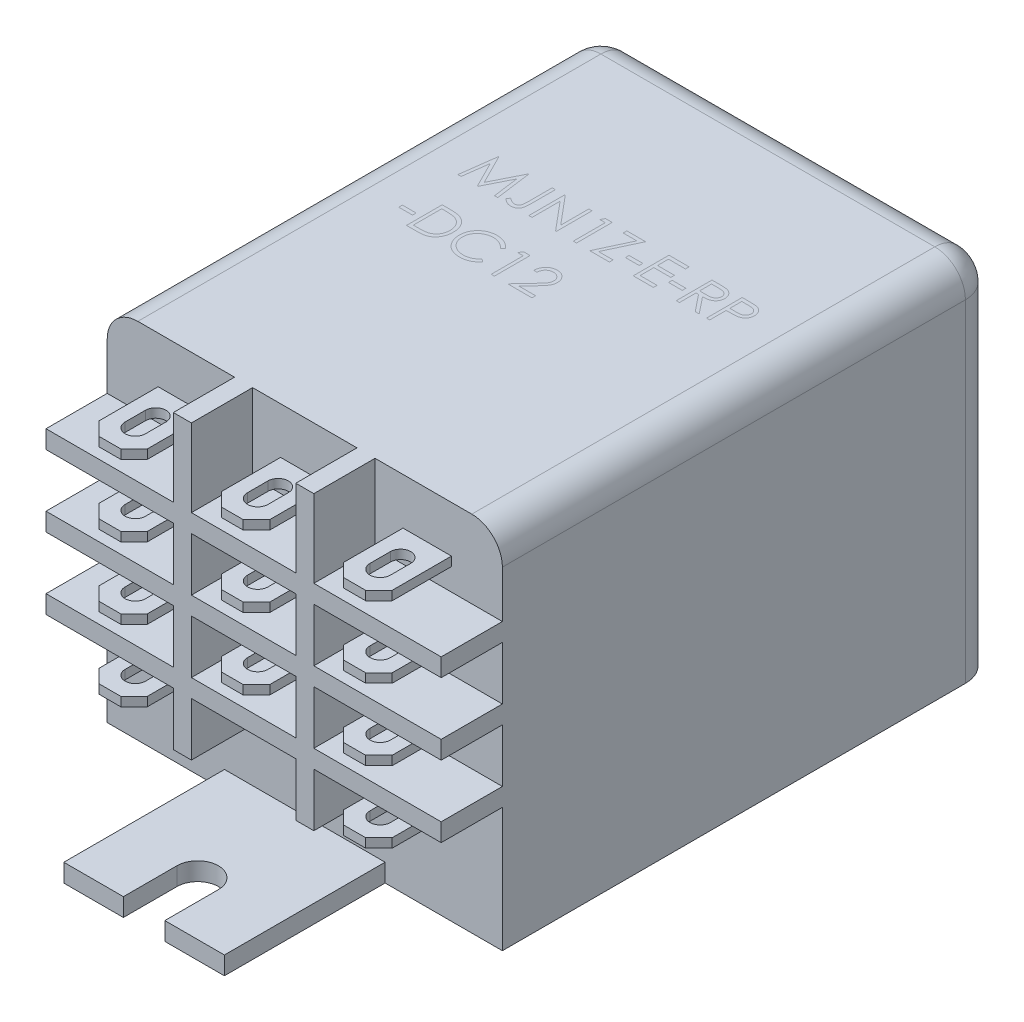
SolidWorks part; units mm, degrees
material "ABS"
ref_plane "Ground_Plane" through (0, 0, 0) normal (0, 0, 1) x (1, 0, 0)
ref_plane "VehicleCentre_Plane" through (0, 0, 0) normal (0, 1, 0) x (1, 0, 0)
ref_plane "FrontAxle_Plane" through (0, 0, 0) normal (1, 0, 0) x (0, 0, -1)
sketch "Sketch1" plane through (0, 0, 0) normal (0, 1, 0) x (1, 0, 0)
  line L1 (19.365, 24.19) -> (-19.365, 24.19)
  line L2 (19.365, 24.19) -> (19.365, -24.19)
  line L3 (19.365, -24.19) -> (-19.365, -24.19)
  line L4 (-19.365, 24.19) -> (-19.365, -24.19)
  line L5 (19.365, 24.19) -> (-19.365, -24.19) construction
  line L6 (19.365, -24.19) -> (-19.365, 24.19) construction
  point P0 (0, 0)
  dimension "D1" = 38.73
  dimension "D2" = 48.38
extrude "Boss-Extrude1" add sketch "Sketch1" along normal blind 35.56
sketch "Sketch2" plane through (0, 0, 0) normal (0, 1, 0) x (1, 0, 0)
  line L0 (-7.87, 24.19) -> (7.87, 24.19)
  line L1 (19.365, 24.19) -> (-19.365, 24.19) construction
  line L2 (7.87, 24.19) -> (7.87, 33.72)
  line L3 (7.87, 33.72) -> (2.03, 33.72)
  line L4 (2.03, 33.72) -> (2.03, 28.81)
  line L5 (-7.87, 24.19) -> (-7.87, 33.72)
  line L6 (-7.87, 33.72) -> (-2.03, 33.72)
  line L7 (-2.03, 33.72) -> (-2.03, 28.81)
  line L8 (7.87, -24.19) -> (-7.87, -24.19)
  line L9 (-7.87, -24.19) -> (-7.87, -39.94)
  line L10 (-7.87, -39.94) -> (-2.03, -39.94)
  line L11 (-2.03, -39.94) -> (-2.03, -34.69)
  line L12 (7.87, -24.19) -> (7.87, -39.94)
  line L13 (7.87, -39.94) -> (2.03, -39.94)
  line L14 (2.03, -39.94) -> (2.03, -34.69)
  line L15 (-19.365, -24.19) -> (19.365, -24.19) construction
  arc A0 (-2.03, 28.81) -> (2.03, 28.81) centre (0, 28.81) ccw
  arc A1 (2.03, -34.69) -> (-2.03, -34.69) centre (0, -34.69) ccw
  point P23 (0, 0)
  dimension "D2" = 2.03
  dimension "D1" = 15.74
  dimension "D3" = 9.53
  dimension "D4" = 10.5
  dimension "D5" = 73.66
  dimension "D6" = 63.5
extrude "Boss-Extrude2" add sketch "Sketch2" along normal blind 1.77
sketch "Sketch3" plane through (0, 0, 24.19) normal (0, 0, 1) x (1, 0, 0)
  line L0 (-19.365, 35.56) -> (19.365, 35.56) construction
  line L1 (-2.3749, 31.0045) -> (2.3749, 31.0045)
  line L2 (-2.3749, 31.0045) -> (-2.3749, 30.1155)
  line L3 (-2.3749, 30.1155) -> (2.3749, 30.1155)
  line L4 (2.3749, 31.0045) -> (2.3749, 30.1155)
  line L5 (-2.3749, 31.0045) -> (2.3749, 30.1155) construction
  line L6 (-2.3749, 30.1155) -> (2.3749, 31.0045) construction
  line L7 (9.6251, 31.0045) -> (9.6251, 30.1155)
  line L8 (9.6251, 31.0045) -> (14.3749, 31.0045)
  line L9 (14.3749, 31.0045) -> (14.3749, 30.1155)
  line L10 (9.6251, 30.1155) -> (14.3749, 30.1155)
  line L11 (9.6251, 24.0045) -> (9.6251, 23.1155)
  line L12 (9.6251, 24.0045) -> (14.3749, 24.0045)
  line L13 (14.3749, 24.0045) -> (14.3749, 23.1155)
  line L14 (9.6251, 23.1155) -> (14.3749, 23.1155)
  line L15 (9.6251, 17.0045) -> (9.6251, 16.1155)
  line L16 (9.6251, 17.0045) -> (14.3749, 17.0045)
  line L17 (14.3749, 17.0045) -> (14.3749, 16.1155)
  line L18 (9.6251, 16.1155) -> (14.3749, 16.1155)
  line L19 (9.6251, 10.0045) -> (9.6251, 9.1155)
  line L20 (9.6251, 10.0045) -> (14.3749, 10.0045)
  line L21 (14.3749, 10.0045) -> (14.3749, 9.1155)
  line L22 (9.6251, 9.1155) -> (14.3749, 9.1155)
  line L23 (-2.3749, 24.0045) -> (-2.3749, 23.1155)
  line L24 (-2.3749, 24.0045) -> (2.3749, 24.0045)
  line L25 (2.3749, 24.0045) -> (2.3749, 23.1155)
  line L26 (-2.3749, 23.1155) -> (2.3749, 23.1155)
  line L27 (-2.3749, 17.0045) -> (-2.3749, 16.1155)
  line L28 (-2.3749, 17.0045) -> (2.3749, 17.0045)
  line L29 (2.3749, 17.0045) -> (2.3749, 16.1155)
  line L30 (-2.3749, 16.1155) -> (2.3749, 16.1155)
  line L35 (-2.3749, 31.0045) -> (9.6251, 31.0045) construction
  line L36 (-2.3749, 31.0045) -> (-2.3749, 24.0045) construction
  line L37 (-14.3749, 31.0045) -> (-14.3749, 30.1155)
  line L38 (-14.3749, 31.0045) -> (-9.6251, 31.0045)
  line L39 (-9.6251, 31.0045) -> (-9.6251, 30.1155)
  line L40 (-14.3749, 30.1155) -> (-9.6251, 30.1155)
  line L41 (-14.3749, 24.0045) -> (-14.3749, 23.1155)
  line L42 (-14.3749, 24.0045) -> (-9.6251, 24.0045)
  line L43 (-9.6251, 24.0045) -> (-9.6251, 23.1155)
  line L44 (-14.3749, 23.1155) -> (-9.6251, 23.1155)
  line L45 (-14.3749, 17.0045) -> (-14.3749, 16.1155)
  line L46 (-14.3749, 17.0045) -> (-9.6251, 17.0045)
  line L47 (-9.6251, 17.0045) -> (-9.6251, 16.1155)
  line L48 (-14.3749, 16.1155) -> (-9.6251, 16.1155)
  line L49 (-14.3749, 10.0045) -> (-14.3749, 9.1155)
  line L50 (-14.3749, 10.0045) -> (-9.6251, 10.0045)
  line L51 (-9.6251, 10.0045) -> (-9.6251, 9.1155)
  line L52 (-14.3749, 9.1155) -> (-9.6251, 9.1155)
  line L53 (-2.3749, 24.0045) -> (-2.3749, 23.1155) [skipped]
  line L54 (-2.3749, 24.0045) -> (2.3749, 24.0045) [skipped]
  line L55 (2.3749, 24.0045) -> (2.3749, 23.1155) [skipped]
  line L56 (-2.3749, 23.1155) -> (2.3749, 23.1155) [skipped]
  line L57 (-2.3749, 17.0045) -> (-2.3749, 16.1155) [skipped]
  line L58 (-2.3749, 17.0045) -> (2.3749, 17.0045) [skipped]
  line L59 (2.3749, 17.0045) -> (2.3749, 16.1155) [skipped]
  line L60 (-2.3749, 16.1155) -> (2.3749, 16.1155) [skipped]
  line L61 (-2.3749, 10.0045) -> (-2.3749, 9.1155) [skipped]
  line L62 (-2.3749, 10.0045) -> (2.3749, 10.0045) [skipped]
  line L63 (2.3749, 10.0045) -> (2.3749, 9.1155) [skipped]
  line L64 (-2.3749, 9.1155) -> (2.3749, 9.1155) [skipped]
  line L65 (-2.3749, 31.0045) -> (-14.3749, 31.0045) construction
  line L66 (-2.3749, 31.0045) -> (-2.3749, 24.0045) construction
  line L67 (-2.3749, 9.1155) -> (2.3749, 9.1155) [skipped]
  line L68 (-2.3749, 10.0045) -> (-2.3749, 9.1155) [skipped]
  line L69 (-2.3749, 10.0045) -> (2.3749, 10.0045) [skipped]
  line L70 (2.3749, 10.0045) -> (2.3749, 9.1155) [skipped]
  point P0 (0, 30.56)
  point P6 (0, 0)
  point P11 (0, 0)
  point P34 (0, 0)
  dimension "D1" = 0.889
  dimension "D2" = 4.7498
  dimension "D3" = 5
  dimension "D6" = 12
  dimension "D7" = 7
  dimension "D10" = 12
  dimension "D11" = 7
  dimension "D4" = 2
  dimension "D5" = 4
  dimension "D8" = 2
  dimension "D9" = 4
extrude "Boss-Extrude3" add sketch "Sketch3" along normal blind 7.11 separate body
sketch "Sketch4" plane through (0, 31.0045, 0) normal (0, 1, 0) x (1, 0, 0)
  line L0 (-14.8749, -29.5) -> (-12.5749, -31.8)
  line L1 (-12.5749, -31.8) -> (-11.4251, -31.8)
  line L2 (-11.4251, -31.8) -> (-9.1251, -29.5)
  line L3 (-9.1251, -29.5) -> (-9.1251, -32.8)
  line L4 (-9.1251, -32.8) -> (-14.8749, -32.8)
  line L5 (-14.8749, -32.8) -> (-14.8749, -29.5)
  line L6 (-9.6251, -31.3) -> (-14.3749, -31.3) construction
  line L7 (-14.3749, -31.3) -> (-14.3749, -24.19) construction
  line L8 (-9.6251, -31.3) -> (-9.6251, -24.19) construction
  line L9 (-12, -26.8) -> (-12, -28.8) construction
  line L10 (-11, -26.8) -> (-11, -28.8)
  line L11 (-13, -26.8) -> (-13, -28.8)
  line L12 (-2.8749, -32.8) -> (-2.8749, -29.5)
  line L13 (-2.8749, -29.5) -> (-0.5749, -31.8)
  line L14 (-0.5749, -31.8) -> (0.5749, -31.8)
  line L15 (0.5749, -31.8) -> (2.8749, -29.5)
  line L16 (2.8749, -29.5) -> (2.8749, -32.8)
  line L17 (2.8749, -32.8) -> (-2.8749, -32.8)
  line L18 (0, -26.8) -> (0, -28.8) construction
  line L19 (1, -26.8) -> (1, -28.8)
  line L20 (-1, -26.8) -> (-1, -28.8)
  line L21 (9.1251, -32.8) -> (9.1251, -29.5)
  line L22 (9.1251, -29.5) -> (11.4251, -31.8)
  line L23 (11.4251, -31.8) -> (12.5749, -31.8)
  line L24 (12.5749, -31.8) -> (14.8749, -29.5)
  line L25 (14.8749, -29.5) -> (14.8749, -32.8)
  line L26 (14.8749, -32.8) -> (9.1251, -32.8)
  line L27 (12, -26.8) -> (12, -28.8) construction
  line L28 (13, -26.8) -> (13, -28.8)
  line L29 (11, -26.8) -> (11, -28.8)
  line L30 (-14.8749, -32.8) -> (-2.8749, -32.8) construction
  arc A0 (-11, -26.8) -> (-13, -26.8) centre (-12, -26.8) ccw
  arc A1 (-13, -28.8) -> (-11, -28.8) centre (-12, -28.8) ccw
  arc A2 (1, -26.8) -> (-1, -26.8) centre (0, -26.8) ccw
  arc A3 (-1, -28.8) -> (1, -28.8) centre (0, -28.8) ccw
  arc A4 (13, -26.8) -> (11, -26.8) centre (12, -26.8) ccw
  arc A5 (11, -28.8) -> (13, -28.8) centre (12, -28.8) ccw
  point P10 (-12, -27.8)
  point P19 (-12, -31.3)
  point P28 (0, -27.8)
  point P41 (12, -27.8)
  dimension "D7" = 1
  dimension "D1" = 0.5
  dimension "D2" = 0.5
  dimension "D3" = 135
  dimension "D4" = 0.5
  dimension "D5" = 1.8
  dimension "D6" = 1
  dimension "D8" = 2
  dimension "D9" = 3.5
  dimension "D11" = 12
  dimension "D10" = 3
extrude "Cut-Extrude1" cut sketch "Sketch4" against normal blind 26
sketch "Sketch5" plane through (0, 0, 24.19) normal (0, 0, 1) x (1, 0, 0)
  line L0 (-19.365, 27.945) -> (-6.885, 27.945)
  line L1 (-19.365, 35.56) -> (-19.365, 0) construction
  line L2 (-6.885, 27.945) -> (-6.885, 35.56)
  line L3 (-19.365, 35.56) -> (19.365, 35.56) construction
  line L4 (-6.885, 35.56) -> (-5.115, 35.56)
  line L5 (-5.115, 35.56) -> (-5.115, 27.945)
  line L6 (-5.115, 27.945) -> (5.115, 27.945)
  line L7 (5.115, 27.945) -> (5.115, 35.56)
  line L8 (5.115, 35.56) -> (6.885, 35.56)
  line L9 (6.885, 35.56) -> (6.885, 27.945)
  line L10 (6.885, 27.945) -> (19.365, 27.945)
  line L11 (19.365, 35.56) -> (19.365, 0) construction
  line L12 (19.365, 27.945) -> (19.365, 26.175)
  line L13 (19.365, 26.175) -> (6.885, 26.175)
  line L14 (6.885, 26.175) -> (6.885, 20.945)
  line L15 (6.885, 20.945) -> (19.365, 20.945)
  line L16 (19.365, 20.945) -> (19.365, 19.175)
  line L17 (19.365, 19.175) -> (6.885, 19.175)
  line L18 (6.885, 19.175) -> (6.885, 13.945)
  line L19 (6.885, 13.945) -> (19.365, 13.945)
  line L20 (19.365, 13.945) -> (19.365, 12.175)
  line L21 (19.365, 12.175) -> (6.885, 12.175)
  line L22 (6.885, 12.175) -> (6.885, 6.945)
  line L23 (6.885, 6.945) -> (5.115, 6.945)
  line L24 (5.115, 6.945) -> (5.115, 12.175)
  line L25 (5.115, 12.175) -> (-5.115, 12.175)
  line L26 (-5.115, 12.175) -> (-5.115, 6.945)
  line L27 (-5.115, 6.945) -> (-6.885, 6.945)
  line L28 (-6.885, 6.945) -> (-6.885, 12.175)
  line L29 (-6.885, 12.175) -> (-19.365, 12.175)
  line L30 (-19.365, 12.175) -> (-19.365, 13.945)
  line L31 (-19.365, 13.945) -> (-6.885, 13.945)
  line L32 (-6.885, 13.945) -> (-6.885, 19.175)
  line L33 (-6.885, 19.175) -> (-19.365, 19.175)
  line L34 (-19.365, 19.175) -> (-19.365, 20.945)
  line L35 (-19.365, 20.945) -> (-6.885, 20.945)
  line L36 (-6.885, 20.945) -> (-6.885, 26.175)
  line L37 (-6.885, 26.175) -> (-19.365, 26.175)
  line L38 (-19.365, 26.175) -> (-19.365, 27.945)
  line L40 (-5.115, 26.175) -> (5.115, 26.175)
  line L41 (-5.115, 26.175) -> (-5.115, 20.945)
  line L42 (-5.115, 20.945) -> (5.115, 20.945)
  line L43 (5.115, 26.175) -> (5.115, 20.945)
  line L44 (-5.115, 26.175) -> (5.115, 20.945) construction
  line L45 (-5.115, 20.945) -> (5.115, 26.175) construction
  line L46 (-5.115, 19.175) -> (5.115, 19.175)
  line L47 (-5.115, 19.175) -> (-5.115, 13.945)
  line L48 (-5.115, 13.945) -> (5.115, 13.945)
  line L49 (5.115, 19.175) -> (5.115, 13.945)
  line L50 (-5.115, 19.175) -> (5.115, 13.945) construction
  line L51 (-5.115, 13.945) -> (5.115, 19.175) construction
  line L52 (-13.0749, 30.1155) -> (-13.0749, 24.0045) construction
  line L53 (-9.6251, 31.0045) -> (-2.3749, 31.0045) construction
  line L54 (-9.6251, 31.0045) -> (-9.6251, 30.1155) construction
  line L56 (-13.0749, 30.1155) -> (-14.3749, 30.1155) construction
  line L57 (-13.0749, 23.1155) -> (-14.3749, 23.1155) construction
  line L58 (-13.0749, 16.1155) -> (-14.3749, 16.1155) construction
  line L59 (2.3749, 31.0045) -> (2.3749, 30.1155) construction
  point P46 (0, 23.56)
  point P51 (0, 16.56)
  point P58 (-13.0749, 27.06)
  point P59 (-19.365, 27.06)
  point P65 (-6, 35.56)
  point P66 (-9.6251, 30.56)
  point P70 (-13.7249, 30.1155)
  point P75 (-6, 31.0045)
  point P76 (0, 0)
extrude "Boss-Extrude4" add sketch "Sketch5" along normal blind 6
fillet "Fillet1" radius 6 2 edges at (7.87, 0.885, -24.19) (-7.87, 0.885, -24.19)
fillet "Fillet2" radius 3 5 edges at (-19.365, 35.56, 0) (19.365, 35.56, 0) (-19.365, 17.78, -24.19) (19.365, 17.78, -24.19) (0, 35.56, -24.19)
sketch "Sketch6" plane through (0, 35.56, 0) normal (0, 1, 0) x (1, 0, 0)
  text T0 "MJN1Z-E-RP\r\n-DC12"
split line "Split Line1"
equation "\"D3@Sketch5\"=\"D2@Sketch5\""
equation "\"D4@Sketch5\"=\"D2@Sketch5\""
equation "\"D6@Sketch5\"=\"D5@Sketch5\""
